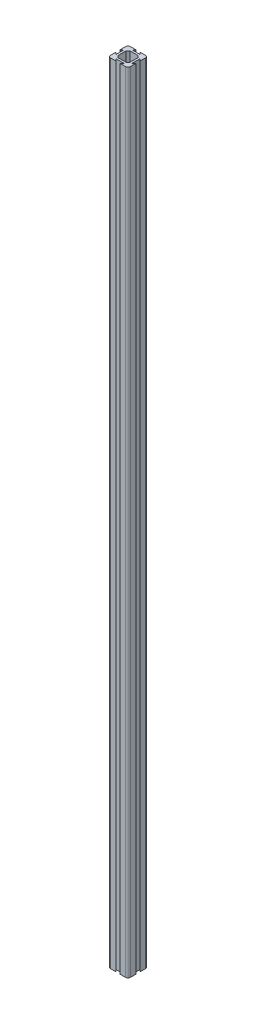
SolidWorks part; units mm, degrees
ref_plane "Front Plane" through (0, 0, 0) normal (0, 0, 1) x (1, 0, 0)
ref_plane "Top Plane" through (0, 0, 0) normal (0, 1, 0) x (1, 0, 0)
ref_plane "Right Plane" through (0, 0, 0) normal (1, 0, 0) x (0, 0, -1)
sketch "Sketch1" plane through (0, 0, 0) normal (0, 1, 0) x (1, 0, 0)
  line L0 (-12.5, 0) -> (12.5, 0) construction
  line L5 (-9.5, 12.5) -> (-2.5, 12.5)
  line L6 (0, -12.5) -> (0, 12.5) construction
  line L11 (-2.5, 12.5) -> (2.5, 12.5) construction
  line L12 (2.5, 12.5) -> (9.5, 12.5)
  line L13 (12.5, 9.5) -> (12.5, 2.5)
  line L14 (12.5, 2.5) -> (12.5, -2.5) construction
  line L15 (12.5, -2.5) -> (12.5, -9.5)
  line L16 (9.5, -12.5) -> (2.5, -12.5)
  line L17 (2.5, -12.5) -> (-2.5, -12.5) construction
  line L18 (-2.5, -12.5) -> (-9.5, -12.5)
  line L19 (-12.5, -9.5) -> (-12.5, -2.5)
  line L20 (-12.5, -2.5) -> (-12.5, 2.5) construction
  line L21 (-12.5, 2.5) -> (-12.5, 9.5)
  line L22 (-12.5, -2.5) -> (-10, -5)
  line L23 (-10, -5) -> (-10, 5)
  line L24 (-10, 5) -> (-12.5, 2.5)
  line L25 (-2.5, 12.5) -> (-5, 10)
  line L26 (-5, 10) -> (5, 10)
  line L27 (5, 10) -> (2.5, 12.5)
  line L28 (12.5, 2.5) -> (10, 5)
  line L29 (10, 5) -> (10, -5)
  line L30 (10, -5) -> (12.5, -2.5)
  line L31 (-2.5, -12.5) -> (-5, -10)
  line L32 (-5, -10) -> (5, -10)
  line L33 (5, -10) -> (2.5, -12.5)
  line L34 (-7.5, 5) -> (-5, 7.5)
  line L39 (-5, 7.5) -> (5, 7.5)
  line L40 (5, 7.5) -> (7.5, 5)
  line L41 (7.5, 5) -> (7.5, -5)
  line L42 (7.5, -5) -> (5, -7.5)
  line L43 (5, -7.5) -> (-5, -7.5)
  line L44 (-5, -7.5) -> (-7.5, -5)
  line L45 (-7.5, -5) -> (-7.5, 5)
  arc A0 (-9.5, -12.5) -> (-12.5, -9.5) centre (-9.5, -9.5) cw
  arc A1 (12.5, -9.5) -> (9.5, -12.5) centre (9.5, -9.5) cw
  arc A2 (9.5, 12.5) -> (12.5, 9.5) centre (9.5, 9.5) cw
  arc A3 (-9.5, 12.5) -> (-12.5, 9.5) centre (-9.5, 9.5) ccw
  point P2 (0, 0)
  point P6 (0, 0)
  point P44 (-7.5, 0)
  dimension "D3" = 3
  dimension "D1" = 25
  dimension "D2" = 5
  dimension "D4" = 5
  dimension "D5" = 45
  dimension "D6" = 2.5
  dimension "D7" = 2.5
extrude "Boss-Extrude1" add sketch "Sketch1" along normal blind 1000
